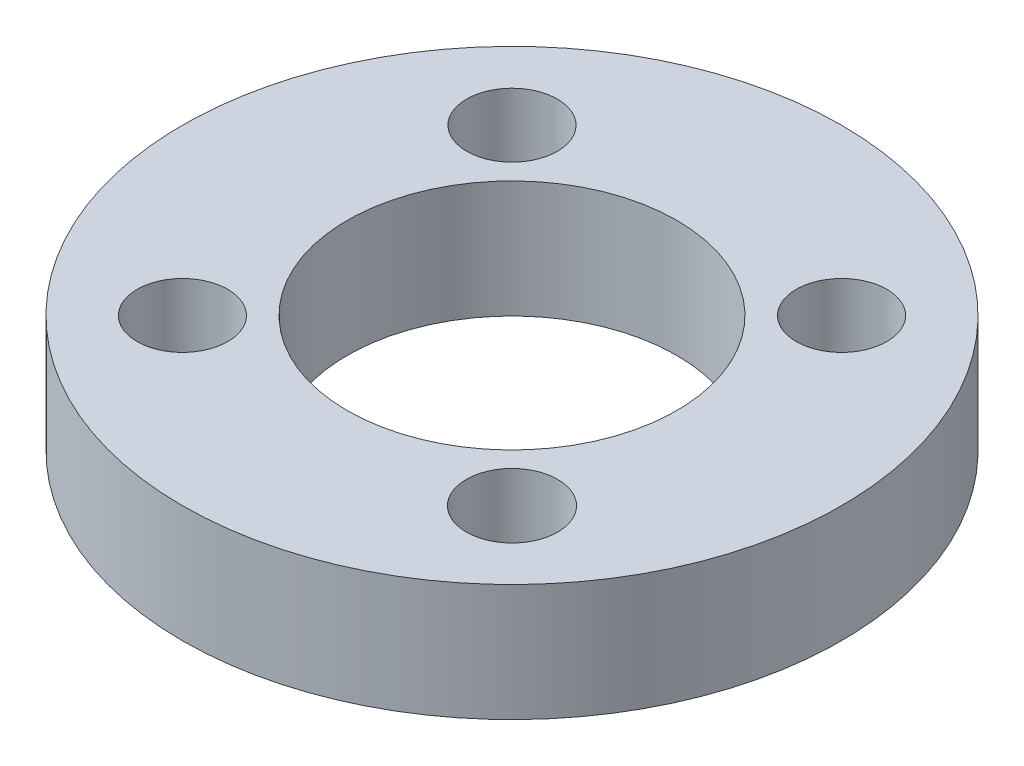
SolidWorks part; units mm, degrees
ref_plane "Front Plane" through (0, 0, 0) normal (0, 0, 1) x (1, 0, 0)
ref_plane "Top Plane" through (0, 0, 0) normal (0, 1, 0) x (1, 0, 0)
ref_plane "Right Plane" through (0, 0, 0) normal (1, 0, 0) x (0, 0, -1)
sketch "Sketch1" plane through (0, 0, 0) normal (0, 1, 0) x (1, 0, 0)
  line L1 (-5, -5) -> (5, -5) construction
  line L2 (-5, -5) -> (-5, 5) construction
  line L3 (-5, 5) -> (5, 5) construction
  line L4 (5, -5) -> (5, 5) construction
  line L5 (-5, -5) -> (5, 5) construction
  line L6 (-5, 5) -> (5, -5) construction
  circle A0 centre (0, 0) radius 10
  circle A1 centre (0, 0) radius 5
  circle A2 centre (-5, -5) radius 1.375
  circle A3 centre (5, -5) radius 1.3864
  circle A5 centre (5, 5) radius 1.375
  circle A7 centre (-5, 5) radius 1.375
  dimension "D1" = 20
  dimension "D2" = 10
  dimension "D5" = 2.75
  dimension "D6" = 2.75
  dimension "D7" = 2.75
  dimension "D3" = 45
  dimension "D4" = 10
extrude "Boss-Extrude1" add sketch "Sketch1" along normal blind 3.55
